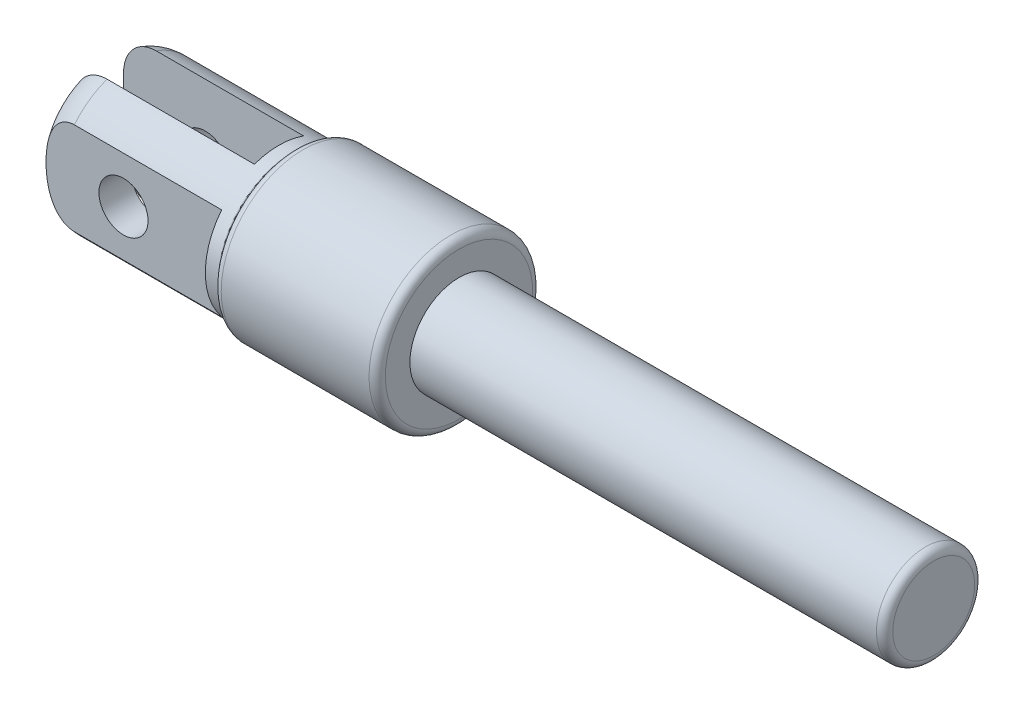
SolidWorks part; units mm, degrees
ref_plane "前视基准面" through (0, 0, 0) normal (0, 0, 1) x (1, 0, 0)
ref_plane "上视基准面" through (0, 0, 0) normal (0, 1, 0) x (1, 0, 0)
ref_plane "右视基准面" through (0, 0, 0) normal (1, 0, 0) x (0, 0, -1)
sketch "草图1" plane through (0, 0, 0) normal (0, 0, 1) x (1, 0, 0)
  line L0 (0, 0) -> (-9, 0) construction
  line L1 (0, 0) -> (0, 3)
  line L2 (0, 3) -> (-29, 3)
  line L3 (-29, 3) -> (-29, 5)
  line L4 (-29, 5) -> (-39, 5)
  line L5 (-39, 5) -> (-39, 4.5)
  line L6 (-39, 4.5) -> (-51, 4.5)
  line L7 (-51, 4.5) -> (-51, 0)
  line L8 (-51, 0) -> (0, 0)
  dimension "D1" = 6
  dimension "D2" = 10
  dimension "D3" = 9
  dimension "D4" = 29
  dimension "D5" = 10
  dimension "D6" = 51
revolve "旋转1" add sketch "草图1" angle 360 about L0
fillet "圆角1" radius 2 1 edges at (-51, 4.5, 0)
sketch "草图2" plane through (-51, 0, 0) normal (-1, 0, 0) x (0, 0, 1)
  line L0 (1.5, 5.8028) -> (3.5, 5.8028)
  line L2 (-1.5, 5.8028) -> (-1.5, -6.1588)
  line L4 (1.5, 5.8028) -> (1.5, -6.1588)
  line L5 (3.5, 5.8028) -> (3.5, -6.1588)
  line L6 (3.5, -6.1588) -> (1.5, -6.1588)
  line L7 (-1.5, 5.8028) -> (-3.5, 5.8028)
  line L8 (-3.5, 5.8028) -> (-3.5, -6.1588)
  line L9 (-3.5, -6.1588) -> (-1.5, -6.1588)
  circle A0 centre (0, 0) radius 7.3214
  dimension "D1" = 2
  dimension "D2" = 3
  dimension "D3" = 2
  dimension "D4" = 1.5
extrude "切除-拉伸1" cut sketch "草图2" against normal blind 11
sketch "草图3" plane through (0, 0, 3.5) normal (0, 0, 1) x (1, 0, 0)
  line L0 (-51, -2) -> (-51, 2) construction
  line L1 (-51, 2) -> (-51, -2) construction
  circle A0 centre (-46, 0) radius 1.5
  point P4 (-51, 0)
  dimension "D1" = 3
  dimension "D2" = 5
extrude "切除-拉伸2" cut sketch "草图3" against normal up to surface (7 mm away) up to face at (-44.068, 0.0547, -3.5)
fillet "圆角2" radius 0.2 1 edges at (-39, 4.5, 0)
fillet "圆角3" radius 0.5 1 edges at (0, 3, 0)
fillet "圆角4" radius 0.5 2 edges at (-29, 5, 0) (-39, 5, 0)
